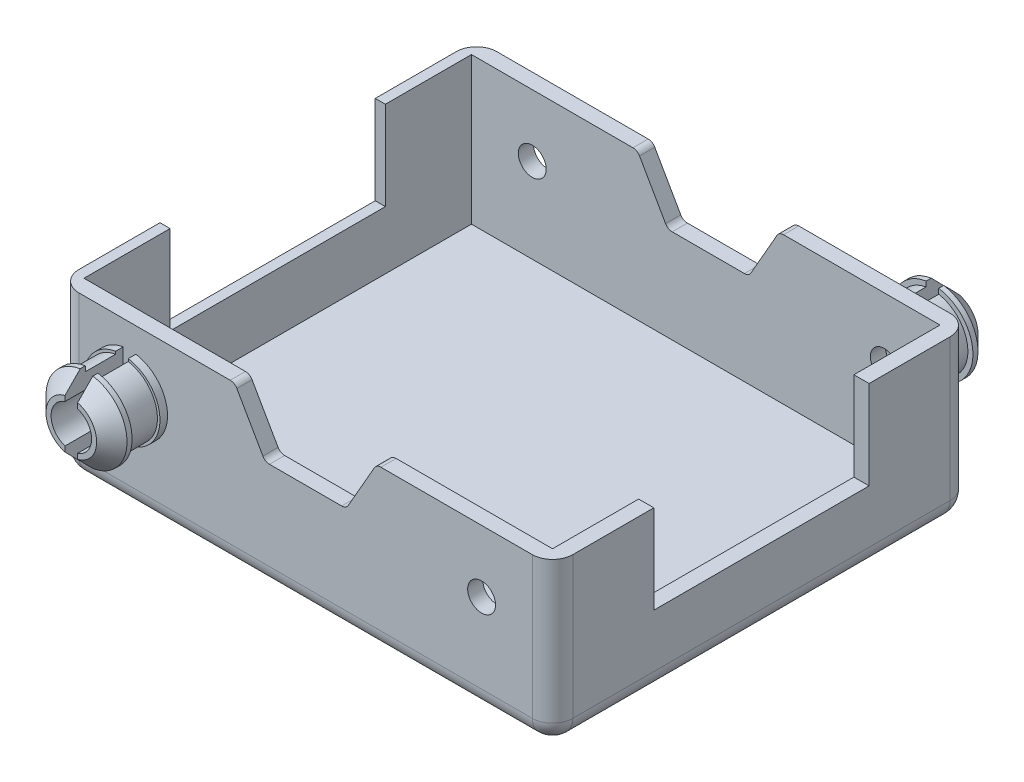
SolidWorks part; units mm, degrees
ref_plane "Front Plane" through (0, 0, 0) normal (0, 0, 1) x (1, 0, 0)
ref_plane "Top Plane" through (0, 0, 0) normal (0, 1, 0) x (1, 0, 0)
ref_plane "Right Plane" through (0, 0, 0) normal (1, 0, 0) x (0, 0, -1)
sketch "Sketch1" plane through (0, 0, 0) normal (0, 1, 0) x (1, 0, 0)
  line L1 (0, 0) -> (97.5, 0)
  line L2 (0, 0) -> (0, 82.5)
  line L3 (0, 82.5) -> (97.5, 82.5)
  line L4 (97.5, 0) -> (97.5, 82.5)
  dimension "D1" = 97.5
  dimension "D2" = 82.5
extrude "Boss-Extrude1" add sketch "Sketch1" along normal blind 32
shell "Shell1" thickness 3
fillet "Fillet1" radius 4 8 edges at (48.75, 0, 0) (97.5, 0, -41.25) (48.75, 0, -82.5) (0, 0, -41.25) (97.5, 16, -82.5) (97.5, 16, 0) (0, 16, -82.5) (0, 16, 0)
sketch "Sketch4" plane through (3, 0, 0) normal (1, 0, 0) x (0, 0, -1)
  line L4 (3, 3) -> (79.5, 3)
  line L5 (79.5, 3) -> (79.5, 32)
  line L6 (79.5, 32) -> (3, 32)
  line L7 (79.5, 3) -> (79.5, 32)
  line L8 (3, 3) -> (79.5, 3)
  line L10 (79.5, 32) -> (3, 32)
  line L12 (3, 32) -> (3, 3)
  line L13 (3, 32) -> (3, 3)
  dimension "D1" = 0
extrude "Cut-Extrude1" cut sketch "Sketch4" along normal blind 83.5 from offset 1 offset against normal yes
sketch "Sketch5" plane through (97.5, 0, 0) normal (1, 0, 0) x (0, 0, -1)
  line L0 (4, 32) -> (78.5, 32) construction
  line L1 (20, 32) -> (62.5, 32)
  line L2 (20, 32) -> (20, 14.5)
  line L3 (20, 14.5) -> (62.5, 14.5)
  line L4 (62.5, 32) -> (62.5, 14.5)
  line L6 (78.5, 0) -> (4, 0) construction
  line L7 (41.25, 4) -> (41.25, 46.3808) construction
  line L8 (4, 4) -> (78.5, 4) construction
  point P12 (41.25, 14.5)
  dimension "D1" = 42.5
  dimension "D2" = 14.5
extrude "Cut-Extrude2" cut sketch "Sketch5" against normal up to surface (97.5 mm away) up to face at (0, 18, -41.25)
sketch "Sketch6" plane through (0, 0, 0) normal (0, 0, 1) x (1, 0, 0)
  line L0 (4, 32) -> (93.5, 32) construction
  line L1 (40.75, 21.5) -> (56.75, 21.5)
  line L4 (56.75, 21.5) -> (56.75, 32) construction
  line L5 (40.75, 21.5) -> (48.75, 32) construction
  line L6 (48.75, 32) -> (56.75, 21.5) construction
  line L7 (56.75, 21.5) -> (62.75, 32)
  line L8 (40.75, 21.5) -> (34.75, 32)
  line L9 (34.75, 32) -> (62.75, 32)
  point P0 (48.75, 32)
  dimension "D1" = 8
  dimension "D2" = 14
  dimension "D3" = 14
  dimension "D4" = 10.5
extrude "Cut-Extrude3" cut sketch "Sketch6" against normal up to surface (82.5 mm away) up to face at (48.75, 18, -82.5)
fillet "Fillet2" radius 1.5 8 edges at (62.75, 32, -81) (56.75, 21.5, -81) (34.75, 32, -81) (40.75, 21.5, -81) (62.75, 32, -1.5) (56.75, 21.5, -1.5) (34.75, 32, -1.5) (40.75, 21.5, -1.5)
sketch "Sketch7" plane through (0, 0, 0) normal (0, 0, 1) x (1, 0, 0)
  line L1 (4, 4) -> (93.5, 4) construction
  line L2 (4, 32) -> (4, 4) construction
  line L3 (48.75, 4) -> (48.75, 37.0086) construction
  circle A0 centre (14, 19.75) radius 2.75
  circle A2 centre (83.5, 19.75) radius 2.75
  point P2 (14, 17)
  dimension "D1" = 5.5
  dimension "D2" = 13
  dimension "D4" = 10
extrude "Cut-Extrude4" cut sketch "Sketch7" against normal up to surface (82.5 mm away)
sketch "Sketch8" plane through (0, 0, 0) normal (0, 0, 1) x (1, 0, 0)
  line L0 (14, 19.75) -> (14, 30.7129) construction
  line L1 (12.75, 32) -> (12.75, 0) construction
  line L2 (4, 32) -> (33.8795, 32) construction
  line L3 (93.5, 0) -> (4, 0) construction
  line L4 (15.25, 32) -> (15.25, 0) construction
  circle A0 centre (14, 19.75) radius 8
  circle A2 centre (14, 19.75) radius 6
  circle A4 centre (14, 19.75) radius 5
  dimension "D1" = 16
  dimension "D2" = 3
  dimension "D3" = 1
  dimension "D4" = 1.25
  dimension "D5" = 2.5
sketch "Sketch9" plane through (0, 0, 0) normal (0, 0, 1) x (1, 0, 0)
  circle A0 centre (14, 19.75) radius 7.5
  circle A1 centre (14, 19.75) radius 2.75 construction
  circle A2 centre (14, 19.75) radius 2.75
  dimension "D1" = 15
extrude "Boss-Extrude3" add sketch "Sketch9" along normal blind 1.5
ref_axis "Axis1" through (14, 19.75, 0) along (0, 0, 1)
ref_plane "Plane1" through (14, 0, 0) normal (-1, 0, 0) x (0, 0, 1)
sketch "Sketch10" plane through (14, 0, 0) normal (-1, 0, 0) x (0, 0, 1)
  line L0 (0, 19.75) -> (33.8718, 19.75) construction
  line L1 (0, 32) -> (0, 0) construction
  line L2 (0, 19.75) -> (69.0457, 19.75) construction
  line L4 (11.5, 24.75) -> (8.5, 27.75)
  line L5 (8.5, 27.75) -> (7.5, 27.75)
  line L6 (7.5, 27.75) -> (7.5, 26.75)
  line L10 (1.5, 23.75) -> (11.5, 23.75)
  line L11 (11.5, 24.75) -> (11.5, 29.847) construction
  line L12 (8.5, 27.75) -> (15.1697, 21.0803) construction
  line L13 (11.5, 24.75) -> (11.5, 23.75)
  line L14 (7.5, 26.75) -> (1.5, 26.75)
  line L15 (1.5, 12.25) -> (1.5, 27.25) construction
  line L16 (1.5, 26.75) -> (1.5, 23.75)
  dimension "D1" = 1
  dimension "D2" = 1
  dimension "D3" = 4
  dimension "D4" = 135
  dimension "D5" = 1
  dimension "D6" = 8
  dimension "D7" = 10
revolve "Revolve1" add sketch "Sketch10" angle 360 about axis through (14, 19.75, 0) along (0, 0, 1)
sketch "Sketch11" plane through (0, 0, 0) normal (0, 0, 1) x (1, 0, 0)
  line L2 (12.75, 32) -> (12.75, 0) construction
  line L3 (12.75, 27.75) -> (15.25, 27.75)
  line L4 (15.25, 32) -> (15.25, 0) construction
  line L5 (15.25, 27.75) -> (15.25, 11.75)
  line L6 (15.25, 11.75) -> (12.75, 11.75)
  line L7 (12.75, 11.75) -> (12.75, 27.75)
extrude "Cut-Extrude5" cut sketch "Sketch11" along normal up to surface (11.5 mm away) up to face at (9, 19.75, 11.5)
ref_plane "Plane2" through (48.25, 0, 0) normal (-1, 0, 0) x (0, 0, 1)
ref_plane "Plane3" through (0, 0, -41.25) normal (0, 0, 1) x (1, 0, 0)
ref_plane "Plane4" through (44.75, 0, -44.75) normal (-0.7071, 0, 0.7071) x (0.7071, 0, 0.7071)
mirror "Mirror2" about plane through (48.25, 0, 0) normal (-1, 0, 0) of "Cut-Extrude5", "Revolve1", "Boss-Extrude3" second plane through (0, 0, -41.25) second plane normal (0, 0, 1)
sketch "Sketch12" plane through (0, 0, -82.5) normal (0, 0, -1) x (-1, 0, 0)
  line L0 (-4, 4) -> (-4, 32) construction
  line L1 (-29.2385, 30.4129) -> (-4, 30.4129)
  line L2 (-29.2385, 30.4129) -> (-29.2385, 7.9541)
  line L3 (-29.2385, 7.9541) -> (-4, 7.9541)
  line L4 (-4, 30.4129) -> (-4, 7.9541)
extrude "Cut-Extrude6" cut sketch "Sketch12" along normal up to surface (11.5 mm away) up to face at (11.125, 19.75, -94)
sketch "Sketch13" plane through (0, 0, 0) normal (0, 0, 1) x (1, 0, 0)
  line L0 (93.5, 4) -> (93.5, 32) construction
  line L1 (61.9909, 29.7891) -> (93.5, 29.7891)
  line L2 (61.9909, 29.7891) -> (61.9909, 10.4496)
  line L3 (61.9909, 10.4496) -> (93.5, 10.4496)
  line L4 (93.5, 29.7891) -> (93.5, 10.4496)
extrude "Cut-Extrude7" cut sketch "Sketch13" along normal up to surface (11.5 mm away)
